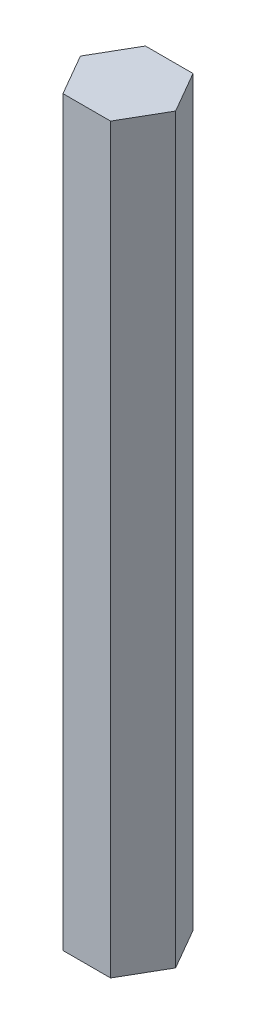
SolidWorks part; units mm, degrees
material "6061-T6 (SS)"
ref_plane "Front Plane" through (0, 0, 0) normal (0, 0, 1) x (1, 0, 0)
ref_plane "Top Plane" through (0, 0, 0) normal (0, 1, 0) x (1, 0, 0)
ref_plane "Right Plane" through (0, 0, 0) normal (1, 0, 0) x (0, 0, -1)
sketch "Sketch1" plane through (0, 0, 0) normal (0, 1, 0) x (1, 0, 0)
  line L1 (3.6662, 6.35) -> (-3.6662, 6.35)
  line L2 (-3.6662, 6.35) -> (-7.3323, 0)
  line L3 (-7.3323, 0) -> (-3.6662, -6.35)
  line L4 (-3.6662, -6.35) -> (3.6662, -6.35)
  line L5 (3.6662, -6.35) -> (7.3323, 0)
  line L6 (7.3323, 0) -> (3.6662, 6.35)
  circle A0 centre (0, 0) radius 6.35 construction
  dimension "D1" = 12.7
extrude "Boss-Extrude1" add sketch "Sketch1" along normal blind 114.3 contours L2 L3 L4 L5 L6 L1
